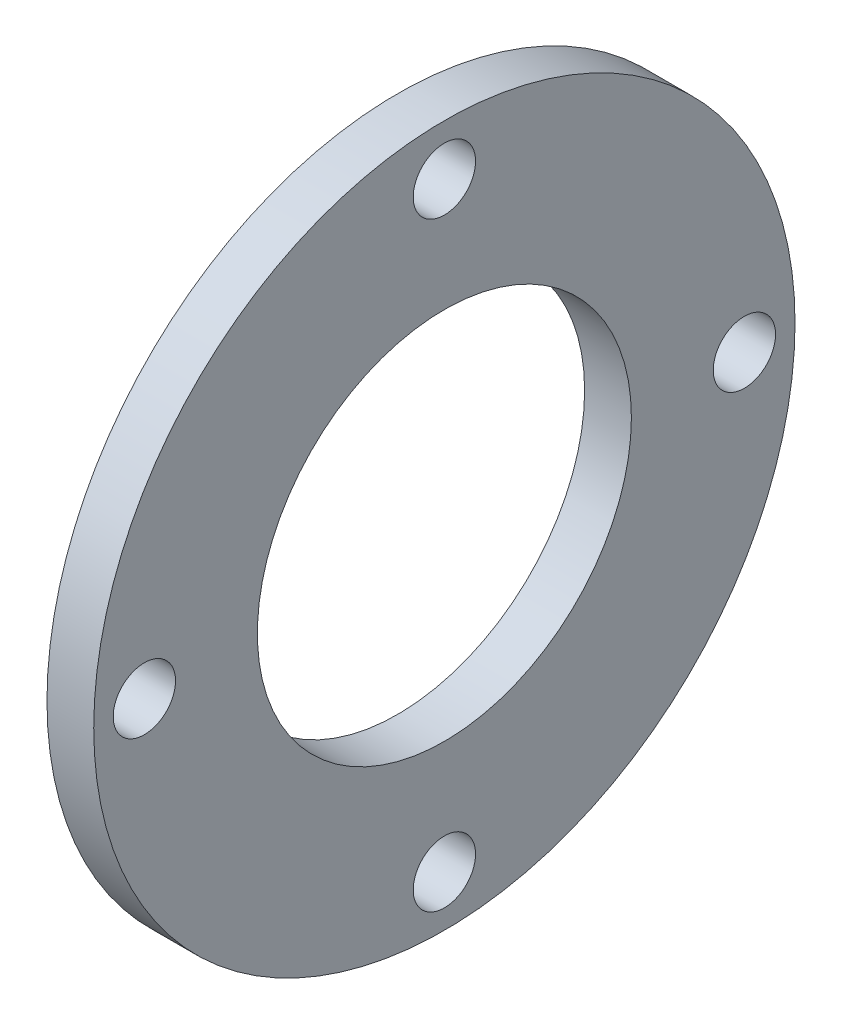
SolidWorks part; units mm, degrees
ref_plane "Front Plane" through (0, 0, 0) normal (0, 0, 1) x (1, 0, 0)
ref_plane "Top Plane" through (0, 0, 0) normal (0, 1, 0) x (1, 0, 0)
ref_plane "Right Plane" through (0, 0, 0) normal (1, 0, 0) x (0, 0, -1)
sketch "Sketch1" plane through (0, 0, 0) normal (1, 0, 0) x (0, 0, -1)
  line L0 (0, 0) -> (0, 19.25) construction
  circle A0 centre (0, 0) radius 22.5
  circle A1 centre (0, 0) radius 12
  circle A2 centre (0, 19.25) radius 2
  circle A3 centre (19.25, 0) radius 2
  circle A4 centre (0, -19.25) radius 2
  circle A5 centre (-19.25, 0) radius 2
  point P15 (0, 0)
  dimension "D1" = 24
  dimension "D2" = 45
  dimension "D3" = 19.25
  dimension "D4" = 4
  dimension "D5" = 19.25
  dimension "D6" = 19.25
extrude "Boss-Extrude1" add sketch "Sketch1" along normal blind 3
